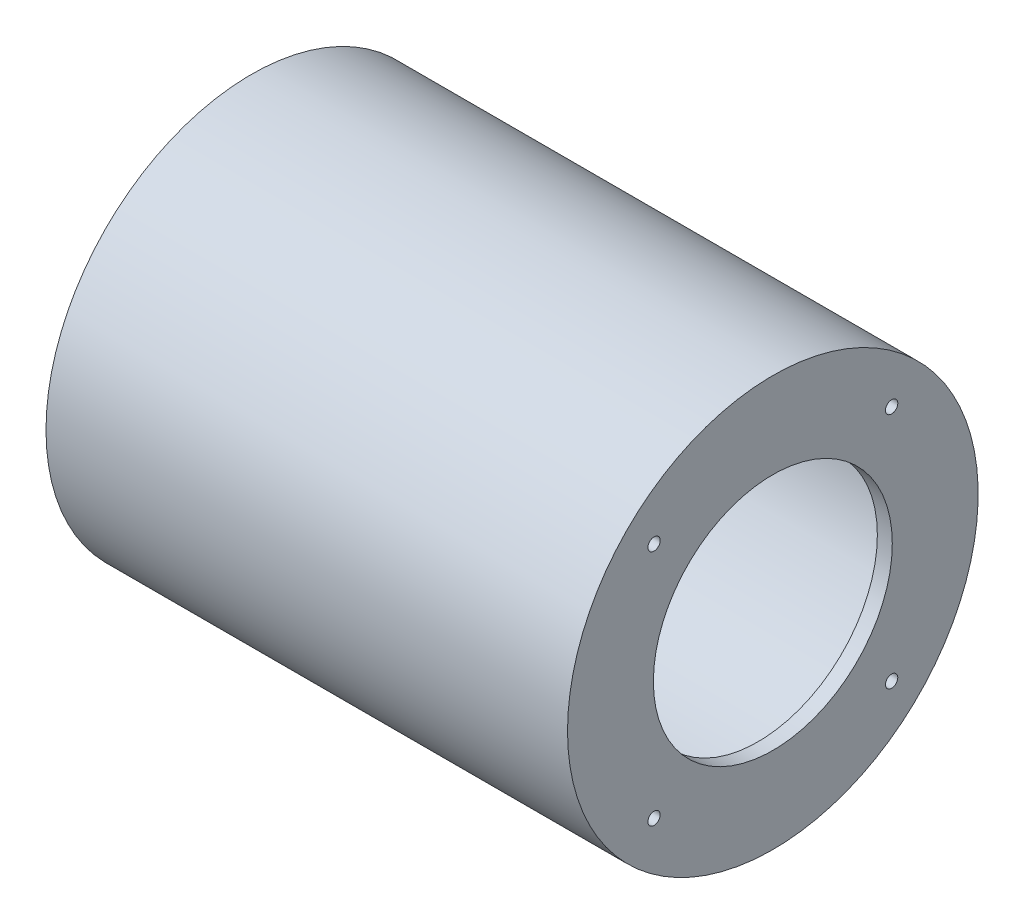
SolidWorks part; units mm, degrees
material "AISI 304"
ref_plane "Front Plane" through (0, 0, 0) normal (0, 0, 1) x (1, 0, 0)
ref_plane "Top Plane" through (0, 0, 0) normal (0, 1, 0) x (1, 0, 0)
ref_plane "Right Plane" through (0, 0, 0) normal (1, 0, 0) x (0, 0, -1)
sketch "Axial profile (mm)" plane through (0, 0, 0) normal (0, 0, 1) x (1, 0, 0)
  line L0 (-110, 0) -> (75, 0) construction
  line L1 (-126, 49) -> (9.7, 49)
  line L2 (9.7, 49) -> (9.7, 32)
  line L3 (9.7, 32) -> (13.7, 32)
  line L4 (13.7, 32) -> (13.7, 55)
  line L5 (13.7, 55) -> (-126, 55)
  line L6 (-126, 55) -> (-126, 49)
revolve "Full revolution" add sketch "Axial profile (mm)" angle 360 about L0
sketch "Sketch2" plane through (0, 0, 0) normal (1, 0, 0) x (0, 0, -1)
  circle A0 centre (-31.8198, 31.8198) radius 1.65
  circle A1 centre (-31.8198, -31.8198) radius 1.65
  circle A2 centre (31.8198, -31.8198) radius 1.65
  circle A3 centre (31.8198, 31.8198) radius 1.65
extrude "Axial holes" cut sketch "Sketch2" along normal blind 4 from offset 9.7
sketch "Sketch3" plane through (0, 0, 0) normal (1, 0, 0) x (0, 0, -1)
  circle A0 centre (0, 52) radius 1.25
  circle A1 centre (-52, 0) radius 1.25
  circle A2 centre (0, -52) radius 1.25
  circle A3 centre (52, 0) radius 1.25
extrude "Cut-Extrude2" cut sketch "Sketch3" along normal blind 6 from offset 126
